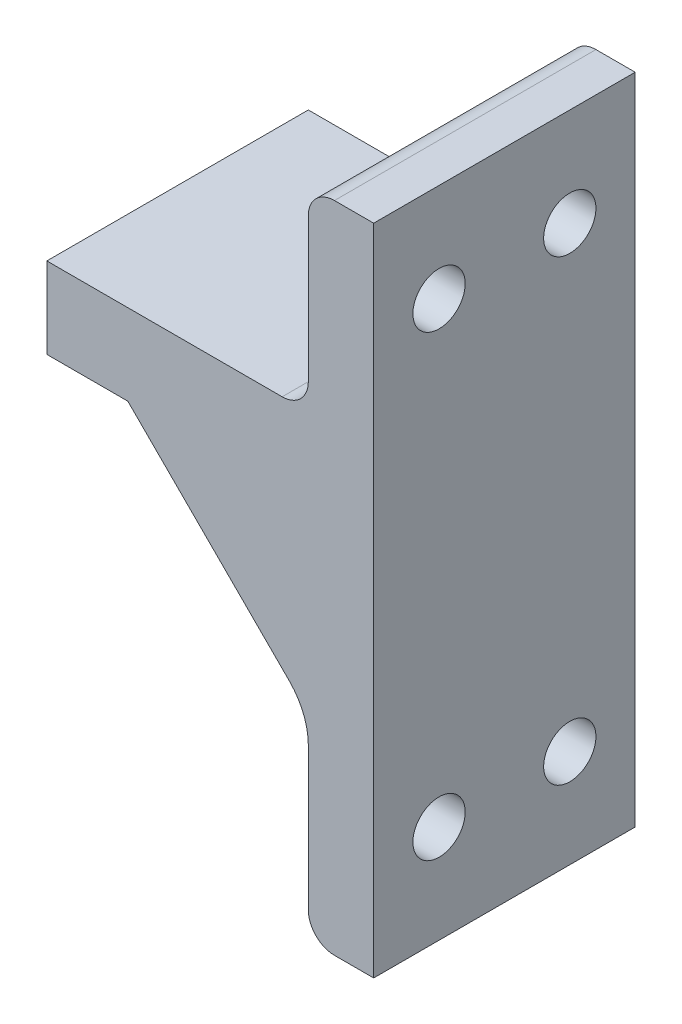
SolidWorks part; units mm, degrees
material "POM 乙缩醛共聚物"
ref_plane "前视基准面" through (0, 0, 0) normal (0, 0, 1) x (1, 0, 0)
ref_plane "上视基准面" through (0, 0, 0) normal (0, 1, 0) x (1, 0, 0)
ref_plane "右视基准面" through (0, 0, 0) normal (1, 0, 0) x (0, 0, -1)
sketch "草图1" plane through (0, 0, 0) normal (0, 0, 1) x (1, 0, 0)
  line L0 (0, 0) -> (0, 50)
  line L1 (0, 50) -> (-5, 50)
  line L2 (-5, 50) -> (-5, 35)
  line L3 (-5, 35) -> (-25, 35)
  line L4 (-25, 35) -> (-5, 15)
  line L5 (-5, 15) -> (-5, 0)
  line L6 (-5, 0) -> (0, 0)
  point P8 (-2.5, 50)
  point P9 (-5, 42.5)
  dimension "D1" = 20
  dimension "D2" = 135
  dimension "D3" = 15
  dimension "D4" = 15
  dimension "D5" = 5
extrude "凸台-拉伸1" add sketch "草图1" along normal blind 20
sketch "草图2" plane through (-5, 0, 0) normal (-1, 0, 0) x (0, 0, 1)
  line L0 (0, 42.5) -> (20, 42.5) construction
  line L1 (0, 50) -> (0, 35) construction
  line L2 (20, 50) -> (20, 35) construction
  line L3 (20, 7.5) -> (0, 7.5) construction
  line L4 (20, 15) -> (20, 0) construction
  line L5 (0, 15) -> (0, 0) construction
  circle A0 centre (5, 42.5) radius 2
  circle A1 centre (15, 42.5) radius 2
  circle A2 centre (5, 7.5) radius 2
  circle A3 centre (15, 7.5) radius 2
  dimension "D1" = 10
  dimension "D2" = 5
  dimension "D3" = 4
  dimension "D4" = 5
  dimension "D5" = 10
extrude "切除-拉伸1" cut sketch "草图2" against normal blind 20
fillet "圆角1" radius 2 3 edges at (-5, 0, 10) (-5, 50, 10) (-5, 35, 10)
fillet "圆角2" radius 5 1 edges at (-5, 15, 10)
sketch "草图3" plane through (0, 0, 0) normal (0, 0, -1) x (-1, 0, 0)
  line L0 (7, 35) -> (25, 35) construction
  line L1 (18.8058, 35) -> (25, 35)
  line L2 (18.8058, 35) -> (18.8058, 28.8058)
  line L3 (18.8058, 28.8058) -> (25, 28.8058)
  line L4 (25, 35) -> (25, 28.8058)
  line L5 (25, 35) -> (6.4645, 16.4645) construction
extrude "凸台-拉伸2" add sketch "草图3" against normal through all
